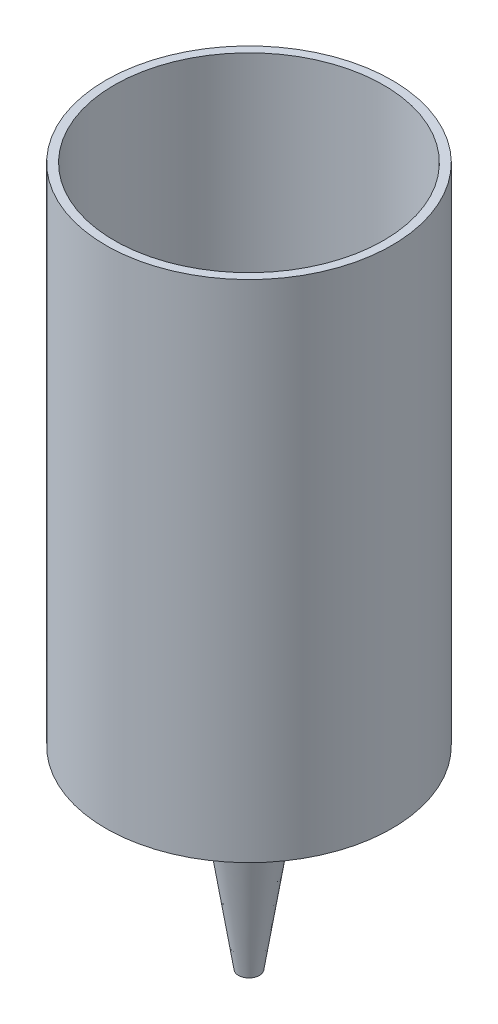
SolidWorks part; units mm, degrees
ref_plane "Front Plane" through (0, 0, 0) normal (0, 0, 1) x (1, 0, 0)
ref_plane "Top Plane" through (0, 0, 0) normal (0, 1, 0) x (1, 0, 0)
ref_plane "Right Plane" through (0, 0, 0) normal (1, 0, 0) x (0, 0, -1)
sketch "Sketch1" plane through (0, 0, 0) normal (0, 0, 1) x (1, 0, 0)
  line L4 (-21.59, 105.41) -> (0, 105.41)
  line L5 (0, 105.41) -> (0, 0)
  line L6 (-21.59, 105.41) -> (-21.59, 29.21)
  line L7 (-21.59, 29.21) -> (-5.5174, 25.4)
  line L8 (-5.5174, 25.4) -> (-1.5875, 0)
  line L9 (-1.5875, 0) -> (0, 0)
  dimension "D1" = 21.59
  dimension "D2" = 76.2
  dimension "D3" = 25.4
  dimension "D4" = 1.5875
  dimension "D5" = 3.81
revolve "Revolve1" add sketch "Sketch1" angle 360 about L5
shell "Shell1" thickness 1.27
sketch "Sketch3" plane through (0, 0, 0) normal (0, -1, 0) x (1, 0, 0)
  circle A0 centre (0, 0) radius 1.0795
  circle A1 centre (0, 0) radius 1.5875 construction
  dimension "D1" = 0.508
extrude "Cut-Extrude1" cut sketch "Sketch3" against normal through all and the other way through all
